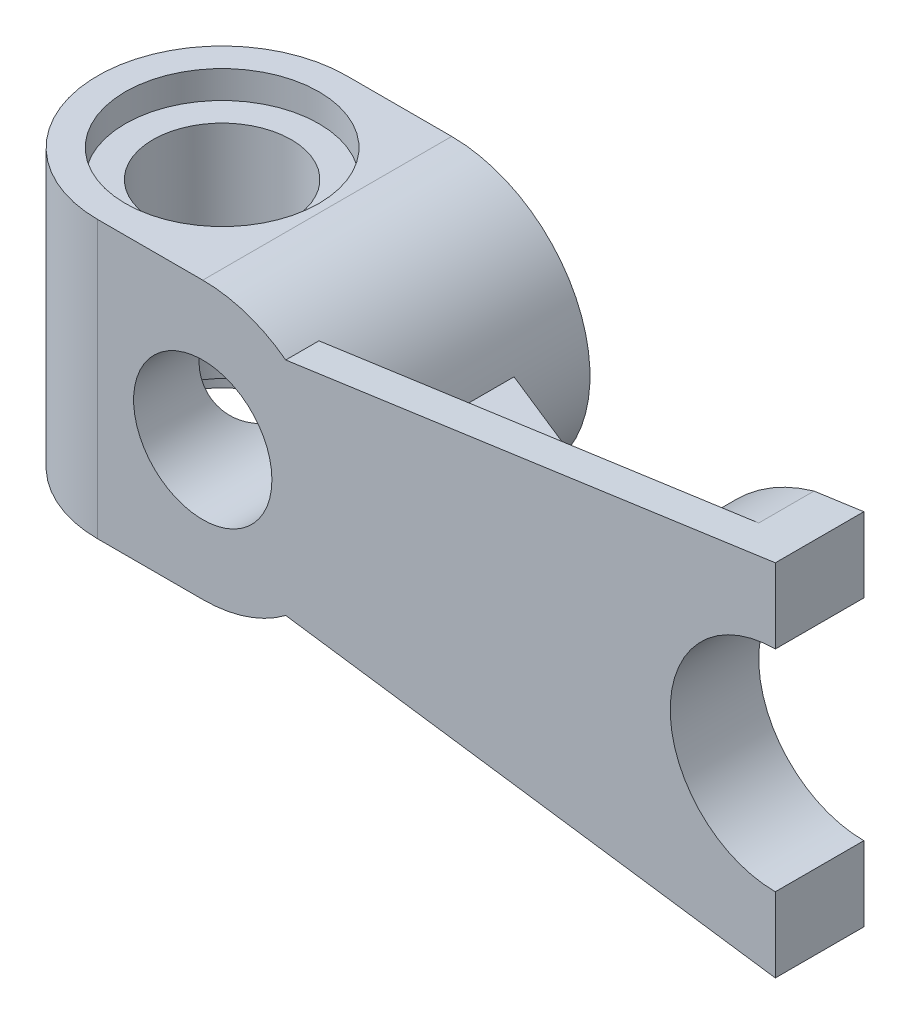
SolidWorks part; units mm, degrees
ref_plane "Front Plane" through (0, 0, 0) normal (0, 0, 1) x (1, 0, 0)
ref_plane "Top Plane" through (0, 0, 0) normal (0, 1, 0) x (1, 0, 0)
ref_plane "Right Plane" through (0, 0, 0) normal (1, 0, 0) x (0, 0, -1)
sketch "Sketch1" plane through (0, 0, 0) normal (0, 0, 1) x (1, 0, 0)
  line L0 (-16.9286, 31.7185) -> (-35.9286, 31.7185)
  line L1 (-16.9286, -18.2815) -> (-35.9286, -18.2815)
  line L2 (-35.9286, 31.7185) -> (-35.9286, -18.2815)
  circle A0 centre (-16.9286, 6.7185) radius 12.5
  arc A1 (-16.9286, -18.2815) -> (-16.9286, 31.7185) centre (-16.9286, 6.7185) ccw
  dimension "D1" = 25
  dimension "D2" = 50
  dimension "D3" = 19
  dimension "D4" = 19
extrude "Boss-Extrude1" add sketch "Sketch1" along normal blind 45
sketch "Sketch2" plane through (0, 31.7185, 0) normal (0, 1, 0) x (1, 0, 0)
  line L1 (-35.9286, 0) -> (-35.9286, -45)
  arc A1 (-35.9286, 0) -> (-35.9286, -45) centre (-35.9286, -22.5) ccw
extrude "Boss-Extrude2" add sketch "Sketch2" against normal blind 50
sketch "Sketch4" plane through (0, 31.7185, 0) normal (0, 1, 0) x (1, 0, 0)
  circle A0 centre (-35.9286, -22.5) radius 17.5
  dimension "D1" = 35
extrude "Cut-Extrude1" cut sketch "Sketch4" against normal blind 5
sketch "Sketch5" plane through (0, -18.2815, 0) normal (0, -1, 0) x (1, 0, 0)
  circle A0 centre (-35.9286, 22.5) radius 17.5
  dimension "D1" = 35
extrude "Cut-Extrude2" cut sketch "Sketch5" against normal blind 5
sketch "Sketch6" plane through (0, -13.2815, 0) normal (0, -1, 0) x (1, 0, 0)
  circle A0 centre (-35.9286, 22.5) radius 12.5
  dimension "D1" = 25
extrude "Cut-Extrude3" cut sketch "Sketch6" against normal blind 96
sketch "Sketch7" plane through (0, 0, 45) normal (0, 0, 1) x (1, 0, 0)
  line L1 (86.5714, 39.2185) -> (86.5714, 25.7185)
  line L2 (86.5714, -12.2815) -> (86.5714, -25.7815)
  arc A0 (86.5714, 39.2185) -> (86.5714, -25.7815) centre (86.5714, 6.7185) ccw
  arc A1 (86.5714, 25.7185) -> (86.5714, -12.2815) centre (86.5714, 6.7185) ccw
  point P4 (-16.9286, 6.7185)
  point P5 (-58.4286, 31.7185)
  dimension "D1" = 65
  dimension "D2" = 38
  dimension "D3" = 0
  dimension "D4" = 145
extrude "Boss-Extrude3" add sketch "Sketch7" against normal blind 16 separate body
sketch "Sketch8" plane through (0, 0, 45) normal (0, 0, 1) x (1, 0, 0)
  line L0 (8.0714, 6.7185) -> (-16.9286, 6.7185) construction
  line L2 (-1.9286, -13.2815) -> (2.0145, -13.2815) construction
  line L3 (-1.9286, 26.7185) -> (86.5714, 39.2185)
  line L4 (-1.9286, -13.2815) -> (86.5714, -25.7815)
  arc A0 (-16.9286, -18.2815) -> (-16.9286, 31.7185) centre (-16.9286, 6.7185) ccw construction
  arc A3 (-16.9286, -18.2815) -> (-16.9286, 31.7185) centre (-16.9286, 6.7185) ccw
  arc A4 (-1.9286, -13.2815) -> (-1.9286, 26.7185) centre (-16.9286, 6.7185) ccw
  arc A5 (86.5714, 39.2185) -> (86.5714, -25.7815) centre (86.5714, 6.7185) ccw
  arc A6 (86.5714, 39.2185) -> (86.5714, -25.7815) centre (86.5714, 6.7185) ccw
  point P12 (-1.9286, -13.2815)
  point P13 (-1.9286, 26.7185)
  dimension "D3" = 3.9431
  dimension "D2" = 0
  dimension "D4" = 0
extrude "Boss-Extrude4" add sketch "Sketch8" against normal blind 6
sketch "Sketch11" plane through (0, 0, 39) normal (0, 0, -1) x (-1, 0, 0)
  line L0 (-8.0714, 6.7185) -> (16.9286, 6.7185) construction
  line L1 (-1.4876, 0.7185) -> (-1.4876, 12.7185) construction
  line L2 (-1.4876, 12.7185) -> (-7.3408, 12.7185) construction
  line L3 (-1.4876, 0.7185) -> (-7.3408, 0.7185) construction
  line L4 (-7.3408, 12.7185) -> (-54.6301, 12.7185)
  line L5 (-7.3408, 0.7185) -> (-54.6301, 0.7185)
  arc A0 (16.9286, 31.7185) -> (16.9286, -18.2815) centre (16.9286, 6.7185) ccw construction
  arc A3 (16.9286, 31.7185) -> (16.9286, -18.2815) centre (16.9286, 6.7185) ccw
  arc A4 (-7.3408, 12.7185) -> (-7.3408, 0.7185) centre (16.9286, 6.7185) ccw
  arc A6 (-77.5702, -24.5101) -> (-77.5702, 37.9472) centre (-86.5714, 6.7185) ccw
  arc A7 (-54.6301, 0.7185) -> (-54.6301, 12.7185) centre (-86.5714, 6.7185) ccw
  point P9 (-1.4876, 6.7185)
  point P14 (-7.3408, 12.7185)
  point P16 (-7.3408, 0.7185)
  dimension "D1" = 12
  dimension "D2" = 6.5838
  dimension "D3" = 0
  dimension "D4" = 0
extrude "Boss-Extrude5" add sketch "Sketch11" along normal blind 26
sketch "Sketch12" plane through (0, 0.7185, 0) normal (0, -1, 0) x (1, 0, 0)
  line L0 (54.6301, 29) -> (54.6301, 32) construction
  line L2 (54.6301, 29) -> (54.6301, 39) construction
  line L3 (54.6301, 32) -> (7.3408, 13)
  line L4 (7.3408, 13) -> (54.6301, 13)
  line L5 (54.6301, 13) -> (54.6301, 32)
  dimension "D1" = 3
extrude "Cut-Extrude6" cut sketch "Sketch12" against normal blind 27
sketch "Sketch16" [suppressed] plane through (0, 0, 45) normal (0, 0, 1) x (1, 0, 0)
  line L0 (75.0384, 39.7638) -> (86.5714, 41.7185)
  line L1 (86.5714, 41.7185) -> (85.6659, 51.7082)
  line L2 (85.6659, 51.7082) -> (69.7245, 46.0652)
  line L3 (69.7245, 46.0652) -> (75.0384, 39.7638)
  arc A0 (86.5714, 41.7185) -> (75.0384, 39.7638) centre (86.5714, 6.7185) ccw construction
extrude "Cut-Extrude7" [suppressed] cut sketch "Sketch16" against normal blind 23
sketch "Sketch17" [suppressed] plane through (0, 0, 45) normal (0, 0, 1) x (1, 0, 0)
  line L0 (67.4329, -25.0377) -> (86.5714, -28.2815)
  line L1 (-1.9286, -13.2815) -> (75.0384, -26.3267) construction
  line L2 (90.6592, -49.3423) -> (51.6579, -41.0243)
  line L3 (51.6579, -41.0243) -> (67.4329, -25.0377)
  arc A0 (86.5714, -28.2815) -> (90.6592, -49.3423) centre (116.6253, -33.3754) ccw
extrude "Cut-Extrude8" [suppressed] cut sketch "Sketch17" against normal blind 23
sketch "Sketch18" [suppressed] plane through (0, 0, 45) normal (0, 0, 1) x (1, 0, 0)
  line L0 (79.8773, 35.9621) -> (86.5714, 36.7185)
  line L1 (-1.9286, 26.7185) -> (79.8773, 35.9621) construction
  line L2 (86.5714, 25.7185) -> (86.5714, 36.7185) construction
  line L3 (86.5714, 36.7185) -> (76.9417, 54.4286)
  line L4 (76.9417, 54.4286) -> (69.5102, 50.4156)
  line L5 (69.5102, 50.4156) -> (79.8773, 35.9621)
extrude "Cut-Extrude9" [suppressed] cut sketch "Sketch18" against normal blind 45
sketch "Sketch19" [suppressed] plane through (0, 0, 45) normal (0, 0, 1) x (1, 0, 0)
  line L0 (79.8773, -22.5251) -> (86.5714, -23.2815)
  line L1 (-1.9286, -13.2815) -> (79.8773, -22.5251) construction
  line L2 (86.5714, -23.2815) -> (86.5714, -12.2815) construction
  line L3 (86.5714, -23.2815) -> (80.133, -71.8401)
  line L4 (80.133, -71.8401) -> (59.1773, -55.9984)
  line L5 (59.1773, -55.9984) -> (79.8773, -22.5251)
  arc A0 (79.8773, -22.5251) -> (86.5714, -23.2815) centre (86.5714, 6.7185) ccw construction
extrude "Cut-Extrude10" [suppressed] cut sketch "Sketch19" against normal blind 45
sketch "Sketch20" [suppressed] plane through (0, 0, 45) normal (0, 0, 1) x (1, 0, 0)
  line L0 (78.5209, 37.1724) -> (86.5714, 38.2185)
  line L1 (-1.9286, 26.7185) -> (78.5209, 37.1724) construction
  line L2 (86.5714, 38.2185) -> (83.0355, 52.3478)
  line L3 (83.0355, 52.3478) -> (63.2678, 50.1183)
  line L4 (63.2678, 50.1183) -> (78.5209, 37.1724)
extrude "Cut-Extrude11" [suppressed] cut sketch "Sketch20" against normal blind 45
sketch "Sketch21" [suppressed] plane through (0, 0, 45) normal (0, 0, 1) x (1, 0, 0)
  line L0 (78.5209, -23.7354) -> (86.5714, -24.7815)
  line L1 (-1.9286, -13.2815) -> (78.5209, -23.7354) construction
  line L2 (86.5714, -24.7815) -> (86.5714, -12.2815) construction
  line L3 (86.5714, -24.7815) -> (80.84, -59.2181)
  line L4 (80.84, -59.2181) -> (61.3339, -43.5517)
  line L5 (61.3339, -43.5517) -> (78.5209, -23.7354)
extrude "Cut-Extrude12" [suppressed] cut sketch "Sketch21" against normal blind 45
sketch "Sketch22" plane through (0, 0, 45) normal (0, 0, 1) x (1, 0, 0)
  line L0 (86.5714, 39.2185) -> (77.5702, 37.9472)
  line L1 (86.5714, 25.7185) -> (86.5714, 39.2185) construction
  line L2 (-1.9286, 26.7185) -> (77.5702, 37.9472) construction
  line L3 (77.5702, 37.9472) -> (65.2, 56.9553)
  line L4 (65.2, 56.9553) -> (110.3833, 52.7936)
  line L5 (110.3833, 52.7936) -> (86.5714, 39.2185)
  arc A0 (86.5714, 39.2185) -> (77.5702, 37.9472) centre (86.5714, 6.7185) ccw construction
extrude "Cut-Extrude13" cut sketch "Sketch22" against normal blind 45
sketch "Sketch23" plane through (0, 0, 45) normal (0, 0, 1) x (1, 0, 0)
  line L0 (86.5714, -25.7815) -> (77.5702, -24.5101)
  line L1 (-1.9286, -13.2815) -> (77.5702, -24.5101) construction
  line L2 (77.5702, -24.5101) -> (41.1459, -43.1526)
  line L3 (41.1459, -43.1526) -> (115.9295, -52.9291)
  line L4 (115.9295, -52.9291) -> (86.5714, -25.7815)
  arc A0 (77.5702, -24.5101) -> (86.5714, -25.7815) centre (86.5714, 6.7185) ccw construction
extrude "Cut-Extrude14" cut sketch "Sketch23" against normal blind 45
